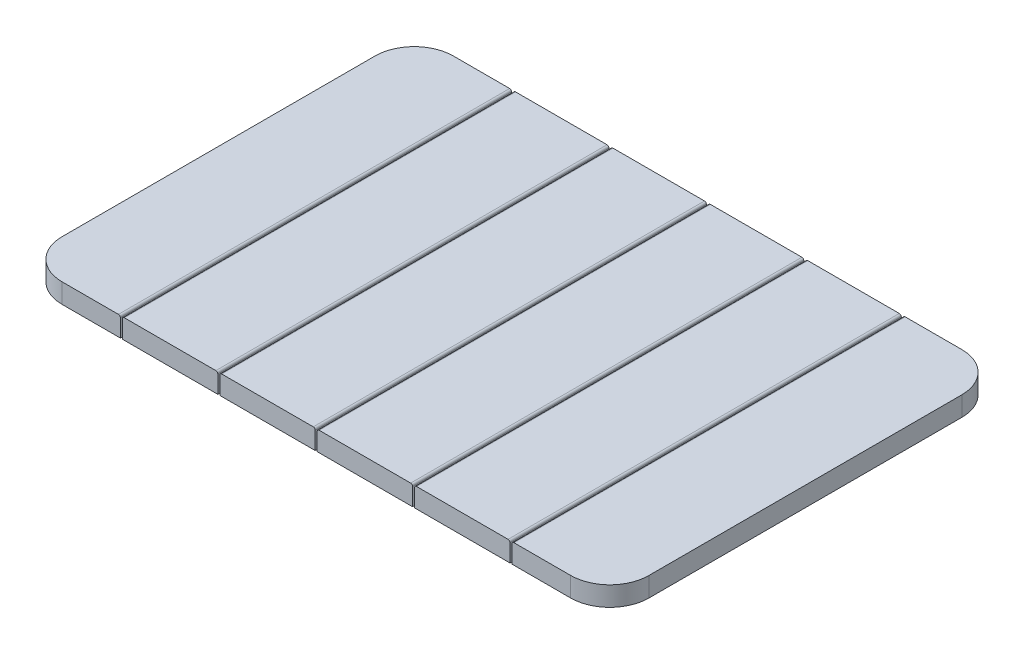
SolidWorks part; units mm, degrees
ref_plane "Alzado" through (0, 0, 0) normal (0, 0, 1) x (1, 0, 0)
ref_plane "Planta" through (0, 0, 0) normal (0, 1, 0) x (1, 0, 0)
ref_plane "Vista lateral" through (0, 0, 0) normal (1, 0, 0) x (0, 0, -1)
sketch "Croquis1" plane through (0, 0, 0) normal (0, 1, 0) x (1, 0, 0)
  line L0 (-501, 500) -> (-501, -500)
  line L1 (650, -500) -> (500, -500)
  line L2 (750, -400) -> (750, 400)
  line L3 (650, 500) -> (500, 500)
  line L4 (-750, -400) -> (-750, 400)
  line L5 (750, -500) -> (-750, 500) construction
  line L6 (750, 500) -> (-750, -500) construction
  line L7 (-496, 500.057) -> (-496, -500)
  line L8 (-252, 500) -> (-252, -500)
  line L9 (-3, 500) -> (-3, -500)
  line L10 (246, 500) -> (246, -500)
  line L11 (495, 500) -> (495, -500)
  line L12 (-247, 500.057) -> (-247, -500)
  line L13 (2, 500.057) -> (2, -500)
  line L14 (251, 500.057) -> (251, -500)
  line L15 (500, 500.057) -> (500, -500)
  line L16 (-501, -500) -> (-650, -500)
  line L17 (-496, -500) -> (-252, -500)
  line L18 (-247, -500) -> (-3, -500)
  line L19 (495, -500) -> (251, -500)
  line L20 (246, -500) -> (-3, -500)
  line L21 (495, 500) -> (251, 500)
  line L22 (246, 500) -> (2, 500)
  line L23 (-3, 500) -> (-247, 500)
  line L24 (-252, 500) -> (-496, 500)
  line L25 (-501, 500) -> (-650, 500)
  arc A0 (650, -500) -> (750, -400) centre (650, -400) ccw
  arc A1 (750, 400) -> (650, 500) centre (650, 400) ccw
  arc A2 (-650, 500) -> (-750, 400) centre (-650, 400) ccw
  arc A3 (-650, -500) -> (-750, -400) centre (-650, -400) cw
  point P0 (0, 0)
  dimension "D3" = 100
  dimension "D1" = 1000
  dimension "D2" = 1500
  dimension "D4" = 249
  dimension "D5" = 5
  dimension "D6" = 5
  dimension "D7" = 5
extrude "Saliente-Extruir3" add sketch "Croquis1" along normal blind 50 contours A3 L16 L0 L25 A2 L4 | L8 L24 L7 L17 | L9 L23 L12 L18 | L10 L22 L13 L20 | L11 L21 L14 L19 | L2 A1 L3 L15 L1 A0
fillet "Redondeo1" radius 5 1 edges at (-501, 50, 0)
fillet "Redondeo2" radius 5 2 edges at (-252, 50, 0) (-496, 50, 0)
fillet "Redondeo3" radius 5 2 edges at (-3, 50, 0) (-247, 50, 0)
fillet "Redondeo4" radius 5 2 edges at (246, 50, 0) (2, 50, 0)
fillet "Redondeo5" radius 5 2 edges at (495, 50, 0) (251, 50, 0)
fillet "Redondeo6" radius 5 1 edges at (500, 50, 0)
